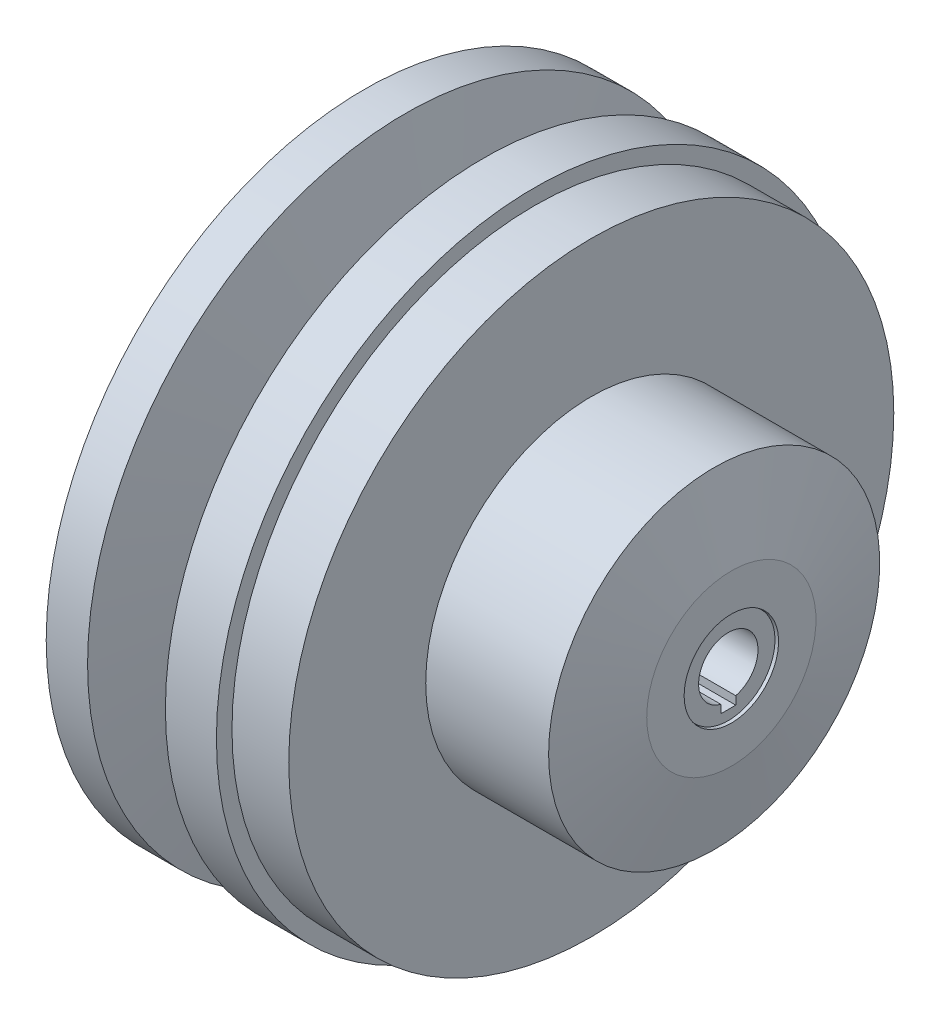
SolidWorks part; units mm, degrees
ref_plane "Front Plane" through (0, 0, 0) normal (0, 0, 1) x (1, 0, 0)
ref_plane "Top Plane" through (0, 0, 0) normal (0, 1, 0) x (1, 0, 0)
ref_plane "Right Plane" through (0, 0, 0) normal (1, 0, 0) x (0, 0, -1)
sketch "Sketch1" plane through (0, 0, 0) normal (0, 0, 1) x (1, 0, 0)
  line L0 (-178.7954, 0) -> (158.9063, 0) construction
  line L1 (-162.9901, 0) -> (-162.9901, 16.125)
  line L2 (-162.9901, 16.125) -> (-163.9901, 16.125)
  line L3 (-163.9901, 16.125) -> (-163.9901, 37.7415)
  line L4 (-163.9901, 37.7415) -> (-160.1231, 37.7415)
  line L5 (-160.1231, 37.7415) -> (-160.1231, 102.185)
  line L6 (-146.8342, 102.185) -> (-160.1231, 102.185)
  line L7 (-133.8342, 30) -> (-134.8342, 30)
  line L8 (-134.3342, 30) -> (-134.3342, 59.1194) construction
  line L9 (-146.8342, 102.185) -> (-134.8342, 30)
  line L10 (-105.445, 102.185) -> (-121.8342, 102.185)
  line L11 (-121.8342, 102.185) -> (-133.8342, 30)
  line L13 (-105.445, 102.185) -> (-105.445, 97.185)
  line L14 (-105.445, 97.185) -> (-87.2066, 97.185)
  line L15 (-87.2066, 97.185) -> (-87.2066, 53.185)
  line L16 (-87.2066, 53.185) -> (-47.733, 53.185)
  line L20 (-42.2066, 27.185) -> (-42.2066, 15.1739)
  line L21 (-42.2066, 15.1739) -> (-43.1901, 14.9934)
  line L22 (-43.1901, 14.9934) -> (-43.1901, 0)
  line L23 (-47.733, 53.185) -> (-42.2066, 27.185)
  line L24 (-162.9901, 0) -> (-43.1901, 0)
  point P20 (-42.2066, 53.185)
  dimension "D1" = 16.125
  dimension "D2" = 1
  dimension "D3" = 3.867
  dimension "D4" = 25
  dimension "D5" = 5
  dimension "D6" = 1
  dimension "D7" = 44
  dimension "D8" = 45
  dimension "D11" = 1
  dimension "D12" = 26
  dimension "D13" = 12
  dimension "D15" = 119.8
revolve "Revolve1" add sketch "Sketch1" angle 360 about L24
sketch "Sketch2" plane through (-162.9901, 0, 0) normal (-1, 0, 0) x (0, 0, 1)
  circle A0 centre (0, 0) radius 15.125
  dimension "D1" = 30.25
extrude "Cut-Extrude5" cut sketch "Sketch2" against normal blind 24.4 contours A0
sketch "Sketch3" plane through (-138.5901, 0, 0) normal (-1, 0, 0) x (0, 0, 1)
  circle A0 centre (0, 0) radius 9.543
  dimension "D1" = 19.086
extrude "Cut-Extrude6" cut sketch "Sketch3" against normal up to next
sketch "Sketch4" plane through (-43.1901, 0, 0) normal (1, 0, 0) x (0, 0, -1)
  line L1 (-2.4, -7.219) -> (2.4, -7.219)
  line L2 (-2.4, -7.219) -> (-2.4, -11.867)
  line L3 (-2.4, -11.867) -> (2.4, -11.867)
  line L4 (2.4, -7.219) -> (2.4, -11.867)
  dimension "D1" = 11.867
  dimension "D2" = 4.8
extrude "Cut-Extrude7" cut sketch "Sketch4" against normal up to next
